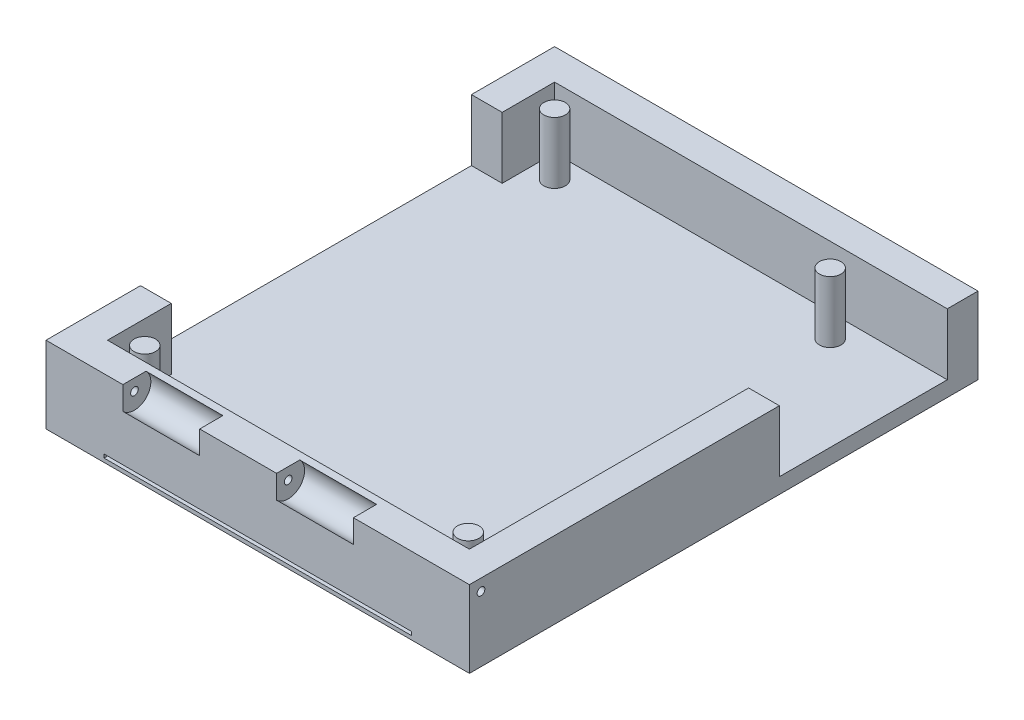
SolidWorks part; units mm, degrees
ref_plane "Front Plane" through (0, 0, 0) normal (0, 0, 1) x (1, 0, 0)
ref_plane "Top Plane" through (0, 0, 0) normal (0, 1, 0) x (1, 0, 0)
ref_plane "Right Plane" through (0, 0, 0) normal (1, 0, 0) x (0, 0, -1)
sketch "Sketch1" plane through (0, 0, 0) normal (0, 1, 0) x (1, 0, 0)
  line L0 (0, 0) -> (0, -58.17)
  line L1 (0, 0) -> (47.09, 0)
  line L2 (0, -58.17) -> (47.09, -58.17)
  line L3 (47.09, 0) -> (47.09, -58.17)
  dimension "D1" = 58.17
  dimension "D2" = 47.09
extrude "Boss-Extrude1" add sketch "Sketch1" along normal blind 2
sketch "Sketch2" plane through (0, 2, 0) normal (0, 1, 0) x (1, 0, 0)
  line L0 (3, -1.6) -> (3, -3)
  line L2 (3, -3) -> (1.6, -3)
  line L3 (3, -3) -> (38.86, -3)
  line L4 (3, -3) -> (3, -56.32)
  line L5 (3, -56.32) -> (45.09, -56.32)
  line L6 (3, -3) -> (3, 0)
  line L7 (47.09, 0) -> (0, 0) construction
  line L8 (3, -3) -> (0, -3)
  line L9 (0, 0) -> (0, -58.17) construction
  circle A0 centre (38.86, -3) radius 1.4
  circle A1 centre (45.09, -56.32) radius 1.4
  circle A2 centre (3, -56.32) radius 1.4
  circle A3 centre (3, -3) radius 1.4
  dimension "D1" = 2.8
  dimension "D2" = 2.8
  dimension "D3" = 2.8
  dimension "D4" = 2.8
  dimension "D5" = 35.86
  dimension "D6" = 53.32
  dimension "D7" = 42.09
  dimension "D8" = 3
  dimension "D9" = 3
extrude "Boss-Extrude2" add sketch "Sketch2" along normal blind 8
sketch "Sketch3" plane through (0, 0, 0) normal (0, 1, 0) x (1, 0, 0)
  line L0 (0, 0) -> (0, -58.17)
  line L1 (0, 0) -> (47.3301, 0)
  line L2 (0, -58.17) -> (47.3301, -58.17)
  line L4 (-4, 4) -> (-4, -62.17)
  line L5 (-4, 4) -> (51.09, 4)
  line L6 (-4, -62.17) -> (51.09, -62.17)
  line L7 (51.09, 4) -> (51.09, -62.17)
  line L8 (23.6651, 0) -> (23.6651, 4)
  line L9 (47.09, 0) -> (47.09, -58.17)
  line L10 (23.6651, -58.17) -> (23.6651, -62.17)
  line L11 (0, -26.4699) -> (-4, -26.4699)
  line L14 (47.09, -29.085) -> (51.09, -29.085)
  dimension "D1" = 4
  dimension "D2" = 4
  dimension "D3" = 4
  dimension "D4" = 4
extrude "Boss-Extrude3" add sketch "Sketch3" along normal blind 10
sketch "Sketch6" plane through (0, 10, 0) normal (0, 1, 0) x (1, 0, 0)
  line L0 (-4, -6.8188) -> (-4, -49.8726)
  line L1 (-4, -6.8188) -> (0.0554, -6.8188)
  line L2 (-4, -49.8726) -> (0.0554, -49.8726)
  line L3 (0.0554, -6.8188) -> (0.0554, -49.8726)
  line L4 (-4, 4) -> (-4, -62.17) construction
  line L6 (47.09, 0) -> (51.09, 0)
  line L7 (47.09, 0) -> (47.09, -21.8439)
  line L8 (51.09, 0) -> (51.09, -21.8439)
  line L9 (47.09, -21.8439) -> (51.09, -21.8439)
  line L10 (51.09, 4) -> (51.09, -62.17) construction
extrude "Cut-Extrude2" cut sketch "Sketch6" against normal blind 8 contours L0 L1 L3 L2 | L6 L7 L9 L8
sketch "Sketch8" plane through (51.09, 0, 0) normal (1, 0, 0) x (0, 0, -1)
  line L0 (-62.17, 10) -> (-62.17, 8.4891)
  line L1 (-62.17, 10) -> (-62.17, 0) construction
  line L2 (-62.17, 8.4891) -> (-60.6624, 8.4891)
  circle A0 centre (-60.6624, 8.4891) radius 0.5
extrude "Cut-Extrude3" cut sketch "Sketch8" against normal through all
ref_plane "Plane1" through (-4, 10, 62.17) normal (1, 0, 0) x (0, 0, -1)
ref_plane "Plane2" through (6, 10, 62.17) normal (1, 0, 0) x (0, 0, -1)
sketch "Sketch10" plane through (6, 10, 62.17) normal (1, 0, 0) x (0, 0, -1)
  circle A0 centre (1.5076, -1.5109) radius 2.1344
extrude "Cut-Extrude4" cut sketch "Sketch10" along normal blind 10
ref_plane "Plane3" through (26, 10, 62.17) normal (1, 0, 0) x (0, 0, -1)
sketch "Sketch11" plane through (26, 10, 62.17) normal (1, 0, 0) x (0, 0, -1)
  circle A0 centre (1.5076, -1.5109) radius 2.1344
extrude "Cut-Extrude5" cut sketch "Sketch11" along normal blind 10
sketch "Sketch12" plane through (0, 0, -4) normal (0, 0, -1) x (-1, 0, 0)
  line L0 (-51.09, 10) -> (-51.09, 7.5132)
  line L1 (-51.09, 10) -> (-51.09, 0) construction
  line L2 (-51.09, 7.5132) -> (-23.54, 7.5132)
  line L3 (-23.54, 7.5132) -> (4, 7.5132)
  line L4 (4, 25.1497) -> (4, -5.1498) construction
  line L5 (-23.54, 7.5132) -> (-18.54, 7.5132)
  line L6 (-18.54, 7.5132) -> (-28.54, 7.5132)
  line L7 (-28.54, 7.5132) -> (-18.54, 7.5132)
  line L8 (-28.54, 7.5132) -> (-28.54, 6.4763)
  line L9 (-18.54, 7.5132) -> (-18.54, 6.4763)
  line L10 (-28.54, 6.4763) -> (-18.54, 6.4763)
  dimension "D1" = 27.55
  dimension "D2" = 5
  dimension "D3" = 5
extrude "Boss-Extrude4" add sketch "Sketch12" along normal blind 2 contours L8 L10 L9 L3 L2
sketch "Sketch13" plane through (0, 0, -4) normal (0, 0, -1) x (-1, 0, 0)
  line L1 (-51.09, 0) -> (4, 0)
  line L2 (4, 0) -> (4, 0.4968)
  line L3 (4, 10) -> (4, 0) construction
  line L4 (4, 0.4968) -> (-3.55, 0.4968)
  line L5 (-3.55, 0.4968) -> (-3.55, 0.9606)
  line L6 (-3.55, 0.9606) -> (-43.54, 0.9606)
  line L7 (-43.54, 0.9606) -> (-43.54, 0.4968)
  line L8 (-43.54, 0.4968) -> (-3.55, 0.4968)
  line L9 (-43.54, 0.4968) -> (-51.09, 0.4968)
  line L10 (-51.09, 10) -> (-51.09, 0) construction
  dimension "D1" = 7.55
  dimension "D2" = 7.55
  dimension "D3" = 39.99
extrude "Cut-Extrude6" cut sketch "Sketch13" against normal through all contours L7 L8 L5 L6
